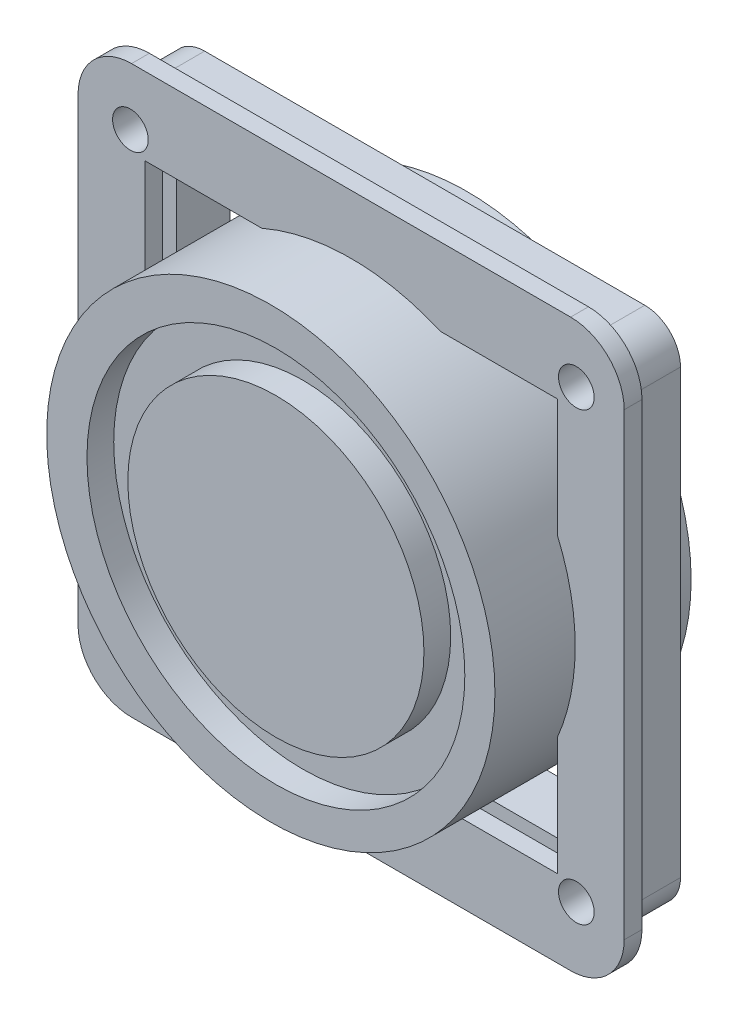
SolidWorks part; units mm, degrees
ref_plane "前视基准面" through (0, 0, 0) normal (0, 0, 1) x (1, 0, 0)
ref_plane "上视基准面" through (0, 0, 0) normal (0, 1, 0) x (1, 0, 0)
ref_plane "右视基准面" through (0, 0, 0) normal (1, 0, 0) x (0, 0, -1)
sketch "草图1" plane through (0, 0, 0) normal (0, 0, 1) x (1, 0, 0)
  line L1 (-8.2472, 7.7459) -> (16.7528, 7.7459) construction
  line L2 (-8.2472, 7.7459) -> (-8.2472, -17.2541) construction
  line L3 (-8.2472, -17.2541) -> (16.7528, -17.2541) construction
  line L4 (16.7528, 7.7459) -> (16.7528, -17.2541) construction
  line L5 (-8.2472, 7.7459) -> (16.7528, -17.2541) construction
  line L6 (-8.2472, -17.2541) -> (16.7528, 7.7459) construction
  line L7 (-10.0854, 9.6391) -> (18.591, 9.6391)
  line L8 (-10.0854, 9.6391) -> (-10.0854, -19.1473)
  line L9 (-10.0854, -19.1473) -> (18.591, -19.1473)
  line L10 (18.591, 9.6391) -> (18.591, -19.1473)
  line L11 (-10.0854, 9.6391) -> (18.591, -19.1473) construction
  line L12 (-10.0854, -19.1473) -> (18.591, 9.6391) construction
  line L13 (-6.6711, 6.1698) -> (15.1767, 6.1698)
  line L14 (-6.6711, 6.1698) -> (-6.6711, -15.678)
  line L15 (-6.6711, -15.678) -> (15.1767, -15.678)
  line L16 (15.1767, 6.1698) -> (15.1767, -15.678)
  line L17 (-6.6711, 6.1698) -> (15.1767, -15.678) construction
  line L18 (-6.6711, -15.678) -> (15.1767, 6.1698) construction
  circle A0 centre (-8.2472, 7.7459) radius 1
  circle A1 centre (16.7528, 7.7459) radius 1
  circle A2 centre (16.7528, -17.2541) radius 1
  circle A3 centre (-8.2472, -17.2541) radius 1
  point P2 (4.2528, -4.7541)
  point P7 (4.2528, -4.7541)
  point P12 (4.2528, -4.7541)
  dimension "D1" = 25
  dimension "D2" = 25
extrude "凸台-拉伸1" add sketch "草图1" along normal blind 3
fillet "圆角1" radius 2 4 edges at (18.591, 9.6391, 1.5) (18.591, -19.1473, 1.5) (-10.0854, -19.1473, 1.5) (-10.0854, 9.6391, 1.5)
sketch "草图2" plane through (0, 0, 3) normal (0, 0, 1) x (1, 0, 0)
  circle A0 centre (4.1239, -4.8829) radius 12.5637
extrude "凸台-拉伸2" add sketch "草图2" along normal mid plane 11
sketch "草图3" plane through (0, 0, 3) normal (0, 0, 1) x (1, 0, 0)
  line L1 (-7.443, 6.6414) -> (15.6909, 6.6414)
  line L2 (-7.443, 6.6414) -> (-7.443, -16.4072)
  line L3 (-7.443, -16.4072) -> (15.6909, -16.4072)
  line L4 (15.6909, 6.6414) -> (15.6909, -16.4072)
  line L5 (-7.443, 6.6414) -> (15.6909, -16.4072) construction
  line L6 (-7.443, -16.4072) -> (15.6909, 6.6414) construction
  line L7 (-11.184, 10.9844) -> (19.4319, 10.9844)
  line L8 (-11.184, 10.9844) -> (-11.184, -20.7503)
  line L9 (-11.184, -20.7503) -> (19.4319, -20.7503)
  line L10 (19.4319, 10.9844) -> (19.4319, -20.7503)
  line L11 (-11.184, 10.9844) -> (19.4319, -20.7503) construction
  line L12 (-11.184, -20.7503) -> (19.4319, 10.9844) construction
  circle A0 centre (-8.2472, 7.7459) radius 1
  circle A1 centre (-8.2472, -17.2541) radius 1
  circle A2 centre (16.7528, -17.2541) radius 1
  circle A3 centre (16.7528, 7.7459) radius 1
  point P12 (4.1239, -4.8829)
  point P18 (4.1239, -4.8829)
extrude "凸台-拉伸3" add sketch "草图3" along normal blind 1
sketch "草图5" plane through (0, 0, 8.5) normal (0, 0, 1) x (1, 0, 0)
  circle A0 centre (4.4084, -4.8829) radius 10.5917
  circle A1 centre (4.4084, -4.8829) radius 8.2998
extrude "切除-拉伸1" cut sketch "草图5" against normal blind 1.5
fillet "圆角2" radius 3 4 edges at (-11.184, -20.7503, 3.5) (19.4319, -20.7503, 3.5) (19.4319, 10.9844, 3.5) (-11.184, 10.9844, 3.5)
